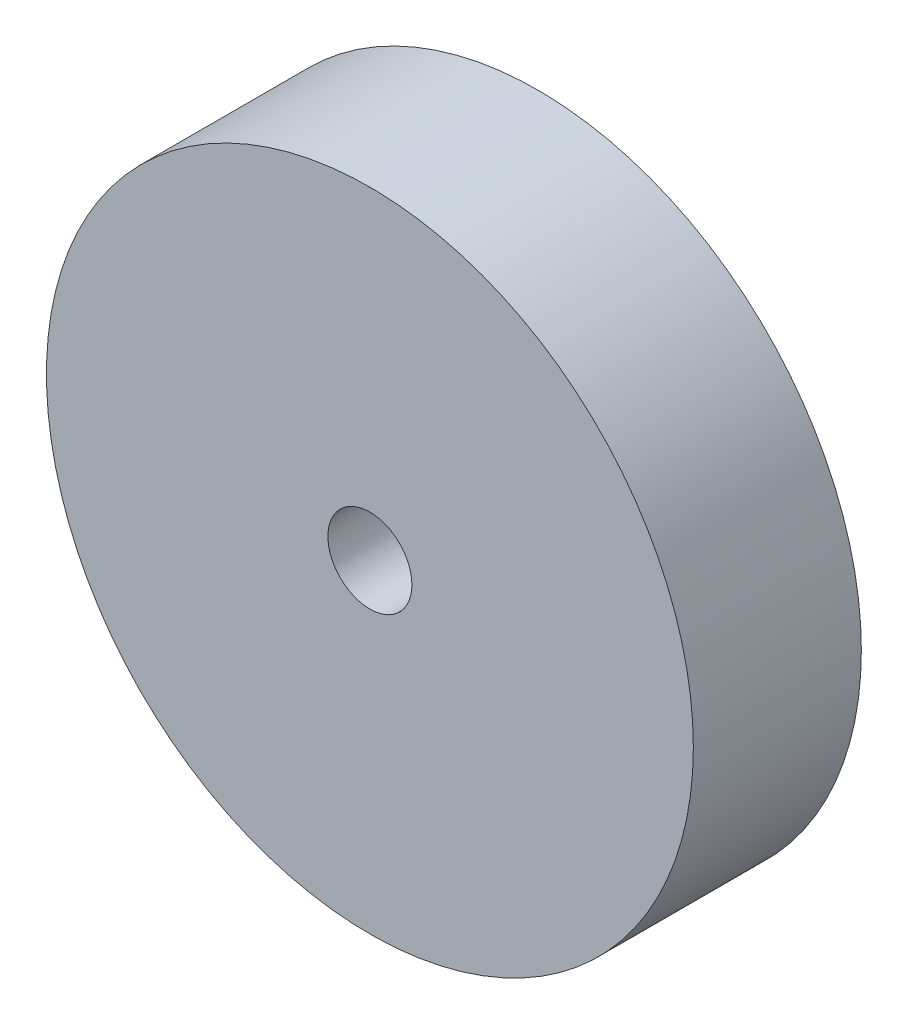
SolidWorks part; units mm, degrees
ref_plane "Front Plane" through (0, 0, 0) normal (0, 0, 1) x (1, 0, 0)
ref_plane "Top Plane" through (0, 0, 0) normal (0, 1, 0) x (1, 0, 0)
ref_plane "Right Plane" through (0, 0, 0) normal (1, 0, 0) x (0, 0, -1)
sketch "Sketch1" plane through (0, 0, 0) normal (0, 0, 1) x (1, 0, 0)
  circle A0 centre (0, 0) radius 3.85
  dimension "D1" = 7.7
extrude "Boss-Extrude1" add sketch "Sketch1" along normal blind 2
sketch "Sketch2" plane through (0, 0, 2) normal (0, 0, 1) x (1, 0, 0)
  circle A0 centre (0, 0) radius 0.5
  dimension "D1" = 1
extrude "Cut-Extrude1" cut sketch "Sketch2" against normal up to next
